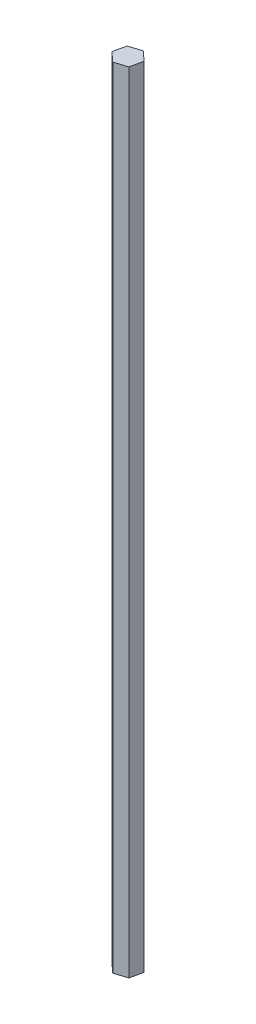
SolidWorks part; units mm, degrees
ref_plane "Front Plane" through (0, 0, 0) normal (0, 0, 1) x (1, 0, 0)
ref_plane "Top Plane" through (0, 0, 0) normal (0, 1, 0) x (1, 0, 0)
ref_plane "Right Plane" through (0, 0, 0) normal (1, 0, 0) x (0, 0, -1)
sketch "Sketch2" plane through (0, 0, 0) normal (0, 1, 0) x (1, 0, 0)
  line L1 (2.1373, -1.9404) -> (2.7491, 0.8807)
  line L2 (2.7491, 0.8807) -> (0.6118, 2.8212)
  line L3 (0.6118, 2.8212) -> (-2.1373, 1.9404)
  line L4 (-2.1373, 1.9404) -> (-2.7491, -0.8807)
  line L5 (-2.7491, -0.8807) -> (-0.6118, -2.8212)
  line L6 (-0.6118, -2.8212) -> (2.1373, -1.9404)
  circle A0 centre (0, 0) radius 2.5 construction
extrude "Boss-Extrude1" add sketch "Sketch2" along normal blind 177.8
